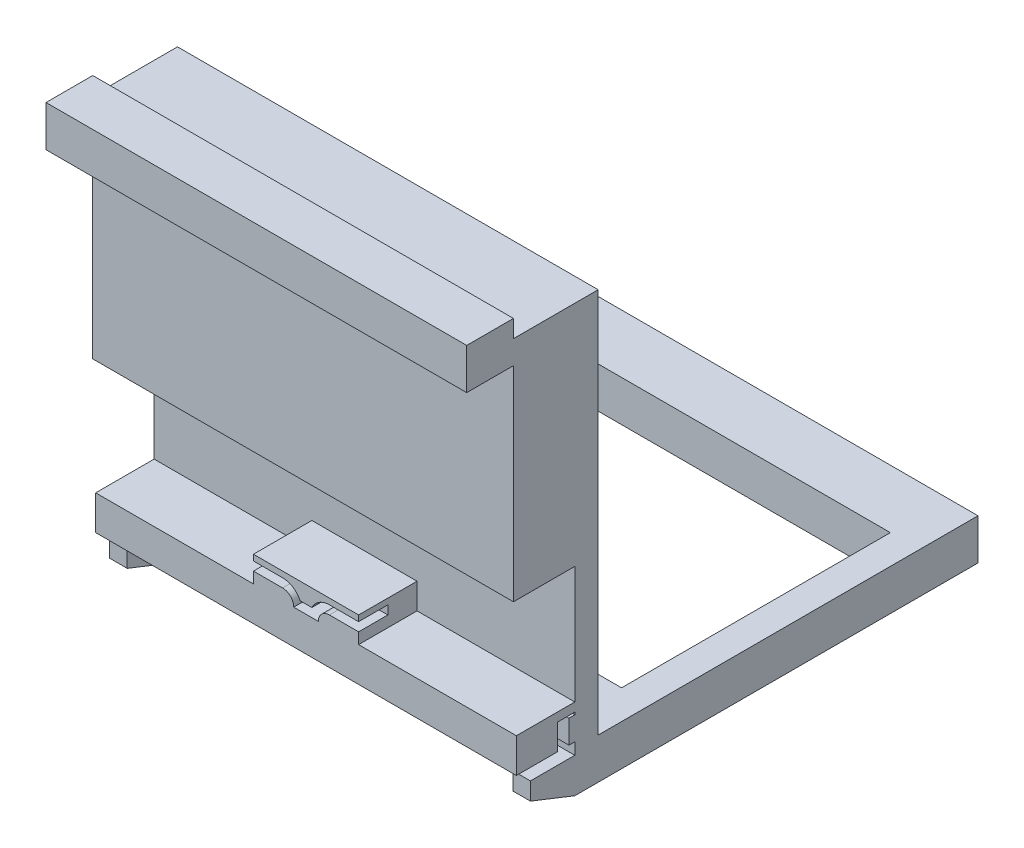
SolidWorks part; units mm, degrees
ref_plane "Alzado" through (0, 0, 0) normal (0, 0, 1) x (1, 0, 0)
ref_plane "Planta" through (0, 0, 0) normal (0, 1, 0) x (1, 0, 0)
ref_plane "Vista lateral" through (0, 0, 0) normal (1, 0, 0) x (0, 0, -1)
sketch "Croquis1" plane through (0, 0, 0) normal (0, 0, 1) x (1, 0, 0)
  line L1 (36, -39.5) -> (-36, -39.5)
  line L5 (36, -39.5) -> (-36, 39.5) construction
  line L6 (36, 39.5) -> (-36, -39.5) construction
  line L7 (-36, -39.5) -> (-33, -39.5)
  line L8 (-36, -39.5) -> (-36, -30.5)
  line L9 (-36, -30.5) -> (-33, -30.5)
  line L10 (-33, -39.5) -> (-33, -30.5)
  line L11 (-36, -30.5) -> (-26.5, -30.5)
  line L12 (-36, -30.5) -> (-36, -27)
  line L13 (-36, -27) -> (-26.5, -27)
  line L14 (-26.5, -30.5) -> (-26.5, -27)
  line L22 (21.8, 10.2) -> (36, 10.2) construction
  line L23 (-36, -27) -> (-36, -23.5) construction
  line L24 (36, -39.5) -> (33, -39.5)
  line L25 (36, -39.5) -> (36, -30.5)
  line L26 (36, -30.5) -> (33, -30.5)
  line L27 (33, -39.5) -> (33, -30.5)
  line L28 (36, -30.5) -> (26.5, -30.5)
  line L29 (36, -30.5) -> (36, -27)
  line L30 (36, -27) -> (26.5, -27)
  line L31 (26.5, -30.5) -> (26.5, -27)
  line L32 (-36, -39.5) -> (-33, -39.5)
  line L33 (-36, -39.5) -> (-36, -32.5)
  line L34 (-36, -32.5) -> (-33, -32.5)
  line L35 (-33, -39.5) -> (-33, -32.5)
  line L36 (36, -39.5) -> (33, -39.5)
  line L37 (36, -39.5) -> (36, -32.5)
  line L38 (36, -32.5) -> (33, -32.5)
  line L39 (33, -39.5) -> (33, -32.5)
  line L40 (36, -22) -> (36, -6) construction
  line L41 (-36, -23.5) -> (36, -23.5)
  line L42 (-36, -23.5) -> (-36, -22)
  line L43 (-36, -22) -> (36, -22)
  line L44 (36, -23.5) -> (36, -22)
  line L45 (-36, -22) -> (36, -22)
  line L49 (-36, -22) -> (-36, 10.2) construction
  line L50 (36, 10.2) -> (36, 17.2) construction
  line L52 (21.8, -6) -> (-21.8, -6)
  line L53 (21.8, -6) -> (21.8, 10.2)
  line L54 (21.8, 10.2) -> (-21.8, 10.2)
  line L55 (-21.8, -6) -> (-21.8, 10.2)
  line L56 (-17.5, 34.5) -> (-36, 34.5)
  line L61 (17.5, 34.5) -> (36, 34.5)
  line L63 (-36, 34.5) -> (36, 34.5)
  line L64 (-36, 34.5) -> (-36, -39.5)
  line L65 (-36, -39.5) -> (36, -39.5)
  line L66 (36, 34.5) -> (36, -39.5)
  line L69 (-17.5, 34.5) -> (17.5, 34.5)
  line L71 (36, 17.2) -> (-36, 17.2)
  line L72 (36, 17.2) -> (36, 34.5)
  line L73 (36, 34.5) -> (-36, 34.5)
  line L74 (-36, 17.2) -> (-36, 34.5)
  point P0 (0, 0)
  point P41 (0, 39.5)
  dimension "D1" = 79
  dimension "D2" = 72
  dimension "D3" = 9
  dimension "D4" = 3
  dimension "D5" = 3.5
  dimension "D6" = 9.5
  dimension "D7" = 9
  dimension "D8" = 3
  dimension "D9" = 3.5
  dimension "D10" = 9.5
  dimension "D11" = 7
  dimension "D12" = 3
  dimension "D13" = 7
  dimension "D14" = 3
  dimension "D15" = 3.5
  dimension "D16" = 1.5
  dimension "D17" = 16
  dimension "D18" = 14.2
  dimension "D19" = 14.2
  dimension "D20" = 16.2
  dimension "D21" = 7
extrude "Saliente-Extruir3" add sketch "Croquis1" along normal blind 4
sketch "Croquis2" plane through (0, 0, 4) normal (0, 0, 1) x (1, 0, 0)
  line L1 (-36, -39.5) -> (-33, -39.5)
  line L2 (-36, -39.5) -> (-36, -33.5)
  line L3 (-36, -33.5) -> (-33, -33.5)
  line L4 (-33, -39.5) -> (-33, -33.5)
  line L5 (36, -39.5) -> (33, -39.5)
  line L6 (36, -39.5) -> (36, -33.5)
  line L7 (36, -33.5) -> (33, -33.5)
  line L8 (33, -39.5) -> (33, -33.5)
  dimension "D1" = 6
  dimension "D2" = 3
  dimension "D3" = 6
  dimension "D4" = 3
extrude "Saliente-Extruir4" add sketch "Croquis2" along normal blind 7.6 contours L2 L1 L4 L3 | L6 L5 L8 L7
sketch "Croquis3" plane through (-36, 0, 0) normal (-1, 0, 0) x (0, 0, 1)
  line L0 (11.6, -33.5) -> (11.6, -36.5) construction
  line L1 (11.6, -39.5) -> (11.6, -33.5) construction
  line L2 (4, -33.5) -> (4, -39.5) construction
  line L3 (11.6, -39.5) -> (0, -39.5) construction
  line L4 (4, -39.5) -> (11.6, -36.5) construction
  line L5 (4, -39.5) -> (11.6, -36.5)
  line L6 (11.6, -36.5) -> (11.6, -39.5)
  line L7 (11.6, -39.5) -> (4, -39.5)
  dimension "D1" = 3
extrude "Cortar-Extruir3" cut sketch "Croquis3" against normal through all contours L7 L5 L6
sketch "Croquis5" plane through (0, 0, 4) normal (0, 0, 1) x (1, 0, 0)
  line L0 (-36, -33.5) -> (-36, -32.5) construction
  line L1 (-36, 34.5) -> (-36, -33.5) construction
  line L2 (36, 34.5) -> (36, -33.5) construction
  line L3 (-36, -32.5) -> (-31, -32.5)
  line L4 (-36, -32.5) -> (-36, -28.5)
  line L5 (-36, -28.5) -> (-31, -28.5)
  line L6 (-31, -32.5) -> (-31, -28.5)
  line L7 (36, -31.5) -> (31, -31.5)
  line L8 (36, -31.5) -> (36, -27.5)
  line L9 (36, -27.5) -> (31, -27.5)
  line L10 (31, -31.5) -> (31, -27.5)
  dimension "D1" = 1
  dimension "D2" = 4
  dimension "D3" = 5
  dimension "D4" = 4
  dimension "D5" = 5
extrude "Saliente-Extruir5" add sketch "Croquis5" along normal blind 1 contours L8 L7 L10 L9 | L4 L3 L6 L5
sketch "Croquis9" plane through (0, 0, 4) normal (0, 0, 1) x (1, 0, 0)
  line L0 (-36, -33.5) -> (-36, -27.1) construction
  line L1 (-36, 34.5) -> (-36, -28.5) construction
  line L2 (36, 34.5) -> (36, -27.5) construction
  line L3 (-36, -27.1) -> (36, -27.1)
  line L4 (-36, -27.1) -> (-36, -25.6)
  line L5 (-36, -25.6) -> (36, -25.6)
  line L6 (36, -27.1) -> (36, -25.6)
  dimension "D1" = 6.4
  dimension "D2" = 1.5
extrude "Saliente-Extruir6" add sketch "Croquis9" along normal blind 8 contours L4 L3 L6 L5
sketch "Croquis10" plane through (0, 0, 12) normal (0, 0, 1) x (1, 0, 0)
  line L1 (-36, -25.6) -> (36, -25.6)
  line L2 (-36, -25.6) -> (-36, -31.5)
  line L3 (-36, -31.5) -> (36, -31.5)
  line L4 (36, -25.6) -> (36, -31.5)
  dimension "D1" = 5.9
extrude "Saliente-Extruir7" add sketch "Croquis10" along normal blind 2
sketch "Croquis11" plane through (0, 0, 14) normal (0, 0, 1) x (1, 0, 0)
  line L1 (-36, -31.5) -> (-26, -31.5)
  line L2 (-36, -31.5) -> (-36, -27.1)
  line L3 (-36, -27.1) -> (-26, -27.1)
  line L4 (-26, -31.5) -> (-26, -27.1)
  line L5 (36, -31.5) -> (26, -31.5)
  line L6 (36, -31.5) -> (36, -27.1)
  line L7 (36, -27.1) -> (26, -27.1)
  line L8 (26, -31.5) -> (26, -27.1)
  dimension "D1" = 4.4
  dimension "D2" = 10
  dimension "D3" = 4.4
  dimension "D4" = 10
extrude "Saliente-Extruir10" add sketch "Croquis11" against normal blind 7
sketch "Croquis14" plane through (0, 0, 4) normal (0, 0, 1) x (1, 0, 0)
  line L0 (-9, -25.6) -> (-9, -23.7)
  line L1 (36, -25.6) -> (-36, -25.6) construction
  line L2 (-9, -21.2) -> (-9, -22.2)
  line L3 (-9, -25.6) -> (9, -25.6)
  line L4 (-9, -25.6) -> (-9, -21.2)
  line L5 (-9, -21.2) -> (9, -21.2)
  line L6 (9, -25.6) -> (9, -21.2)
  line L7 (-9, -23.7) -> (-4, -23.7)
  line L8 (-9, -22.2) -> (-4, -22.2)
  line L9 (-9, -23.7) -> (-2.1, -23.7)
  line L10 (9, -22.2) -> (4, -22.2)
  line L11 (9, -23.7) -> (4, -23.7)
  line L12 (-2.1, -25.6) -> (2.1, -25.6)
  line L13 (9, -23.7) -> (9, -22.2)
  line L14 (-9, -23.7) -> (-9, -22.2)
  line L15 (0, -25.6) -> (0, -24.1)
  line L16 (1, -24.1) -> (-1, -24.1)
  arc A0 (-4, -23.7) -> (-2.1, -25.6) centre (-4, -25.6) cw
  arc A1 (-4, -22.2) -> (-1, -24.1) centre (-4, -25.5184) cw
  arc A2 (4, -23.7) -> (2.1, -25.6) centre (4, -25.6) ccw
  arc A3 (4, -22.2) -> (1, -24.1) centre (4, -25.5184) ccw
  point P25 (0, -24.1)
  dimension "D7" = 5
  dimension "D9" = 1.5
  dimension "D10" = 1
  dimension "D1" = 1.9
  dimension "D2" = 4.4
  dimension "D3" = 18
  dimension "D4" = 1
  dimension "D5" = 5
  dimension "D6" = 5
  dimension "D8" = 5
extrude "Saliente-Extruir14" add sketch "Croquis14" along normal up to surface (10 mm away) up to face at (0, -28.55, 14)
sketch "Croquis15" plane through (0, 0, 4) normal (0, 0, 1) x (1, 0, 0)
  line L1 (-9, -21.2) -> (9, -21.2)
  line L2 (-9, -21.2) -> (-9, -25.6)
  line L3 (-9, -25.6) -> (9, -25.6)
  line L4 (9, -21.2) -> (9, -25.6)
extrude "Saliente-Extruir15" add sketch "Croquis15" along normal blind 5
sketch "Croquis16" plane through (0, 0, 4) normal (0, 0, 1) x (1, 0, 0)
  line L1 (-36, 34.5) -> (36, 34.5)
  line L2 (-36, 34.5) -> (-36, -5.5)
  line L3 (-36, -5.5) -> (36, -5.5)
  line L4 (36, 34.5) -> (36, -5.5)
  line L5 (36, 34.5) -> (36, -25.6) construction
  dimension "D1" = 40
  dimension "D2" = 72
extrude "Saliente-Extruir16" add sketch "Croquis16" along normal blind 10.5
sketch "Croquis17" plane through (0, 0, 14.5) normal (0, 0, 1) x (1, 0, 0)
  line L1 (-36, 34.5) -> (36, 34.5)
  line L2 (-36, 34.5) -> (-36, 29.5)
  line L3 (-36, 29.5) -> (36, 29.5)
  line L4 (36, 34.5) -> (36, 29.5)
  line L5 (36, -5.5) -> (36, 34.5) construction
  dimension "D1" = 5
  dimension "D2" = 72
extrude "Saliente-Extruir17" add sketch "Croquis17" along normal blind 8 contours L2 L1 L4 L3
sketch "Croquis18" plane through (0, 34.5, 0) normal (0, 1, 0) x (1, 0, 0)
  line L1 (-36, -22.5) -> (36, -22.5)
  line L2 (-36, -22.5) -> (-36, -14.5)
  line L3 (-36, -14.5) -> (36, -14.5)
  line L4 (36, -22.5) -> (36, -14.5)
  line L5 (36, -22.5) -> (36, 0) construction
  dimension "D1" = 8
  dimension "D2" = 72
extrude "Saliente-Extruir19" add sketch "Croquis18" along normal blind 2
sketch "Croquis19" plane through (0, 0, 0) normal (0, 0, -1) x (-1, 0, 0)
  line L1 (-36, 34.5) -> (36, 34.5)
  line L2 (-36, 34.5) -> (-36, 33.5)
  line L3 (-36, 33.5) -> (36, 33.5)
  line L4 (36, 34.5) -> (36, 33.5)
  dimension "D1" = 1
  dimension "D2" = 72
extrude "Cortar-Extruir4" cut sketch "Croquis19" against normal blind 14.5
sketch "Croquis20" plane through (0, 0, 0) normal (0, 0, -1) x (-1, 0, 0)
  line L1 (-36, -39.5) -> (36, -39.5)
  line L2 (-36, -39.5) -> (-36, -32.5)
  line L3 (-36, -32.5) -> (36, -32.5)
  line L4 (36, -39.5) -> (36, -32.5)
  dimension "D1" = 7
extrude "Saliente-Extruir20" add sketch "Croquis20" along normal blind 65
sketch "Croquis21" plane through (0, -32.5, 0) normal (0, 1, 0) x (1, 0, 0)
  line L0 (-36, 65) -> (-26, 65) construction
  line L1 (-36, 65) -> (36, 65) construction
  line L2 (-26, 65) -> (-26, 55) construction
  line L3 (-36, 0) -> (-36, 9) construction
  line L4 (-36, 65) -> (-36, 0) construction
  line L5 (-36, 9) -> (-31, 9) construction
  line L6 (-31, 9) -> (31, 9) construction
  line L7 (-26, 9) -> (31, 9)
  line L8 (31, 9) -> (31, 55)
  line L9 (31, 55) -> (-26, 55)
  line L10 (-26, 55) -> (-26, 9)
  dimension "D1" = 10
  dimension "D2" = 10
  dimension "D3" = 9
  dimension "D4" = 5
  dimension "D5" = 62
extrude "Cortar-Extruir5" cut sketch "Croquis21" against normal blind 65
